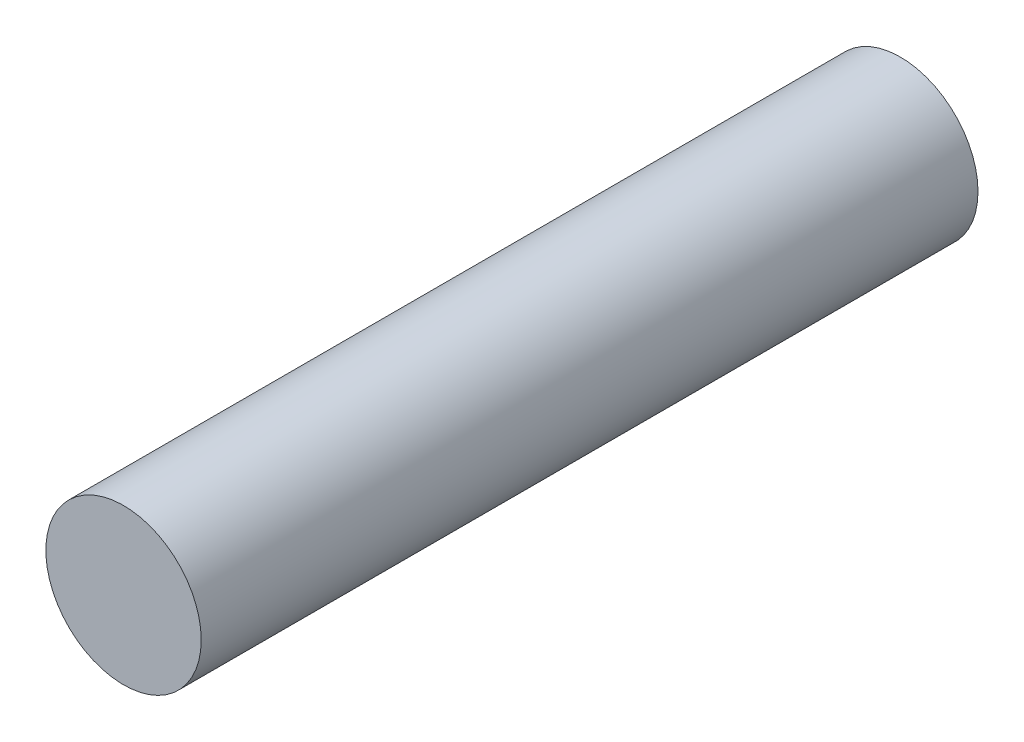
SolidWorks part; units mm, degrees
ref_plane "Front Plane" through (0, 0, 0) normal (0, 0, 1) x (1, 0, 0)
ref_plane "Top Plane" through (0, 0, 0) normal (0, 1, 0) x (1, 0, 0)
ref_plane "Right Plane" through (0, 0, 0) normal (1, 0, 0) x (0, 0, -1)
sketch "Sketch1" plane through (0, 0, 0) normal (0, 0, 1) x (1, 0, 0)
  circle A0 centre (0, 0) radius 100
extrude "Boss-Extrude1" add sketch "Sketch1" along normal blind 1000
